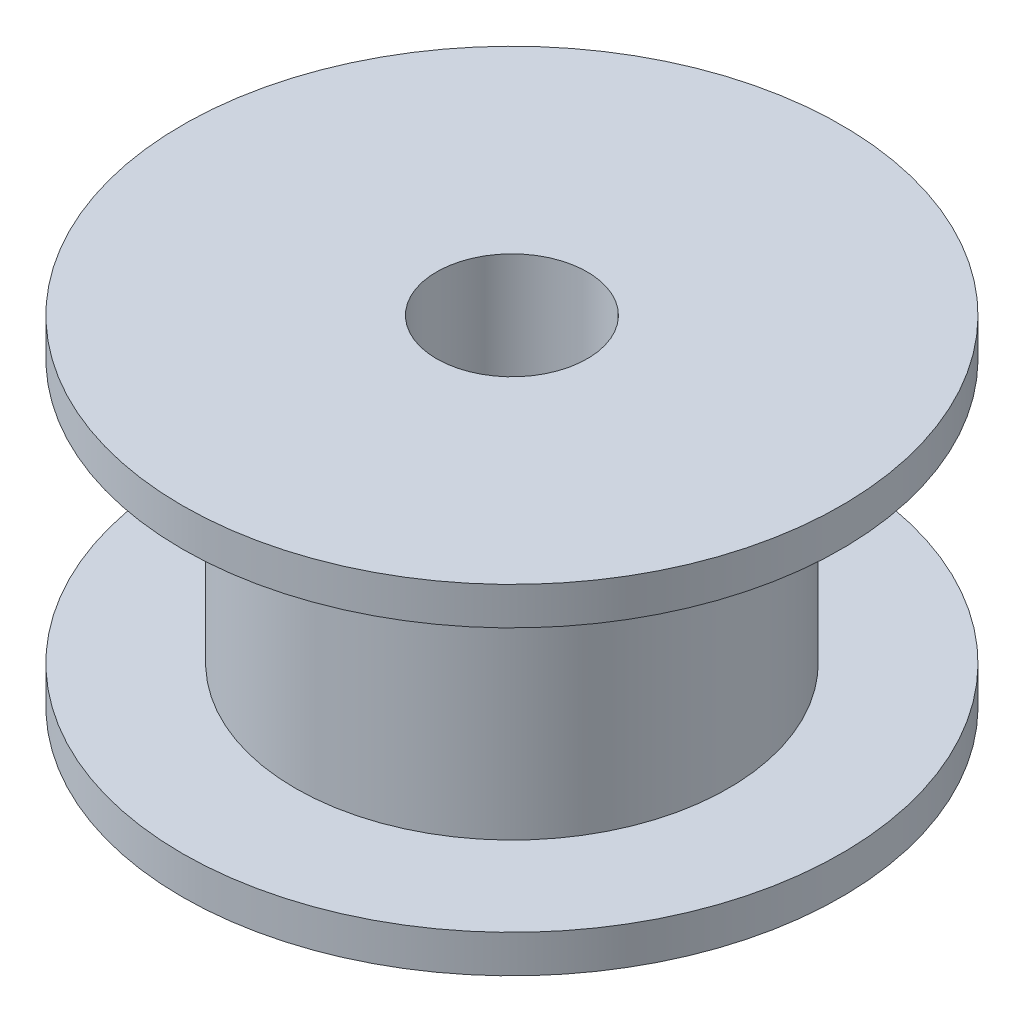
SolidWorks part; units mm, degrees
ref_plane "Спереди" through (0, 0, 0) normal (0, 0, 1) x (1, 0, 0)
ref_plane "Сверху" through (0, 0, 0) normal (0, 1, 0) x (1, 0, 0)
ref_plane "Справа" through (0, 0, 0) normal (1, 0, 0) x (0, 0, -1)
other "Configuration Table"
sketch "Sketch1" plane through (0, 0, 0) normal (0, 0, 1) x (1, 0, 0)
  line L0 (0, 0) -> (2, 0) construction
  line L1 (2, 0) -> (8.75, 0)
  line L2 (8.75, 0) -> (8.75, -1)
  line L3 (8.75, -1) -> (5.75, -1)
  line L4 (5.75, -1) -> (5.75, -8)
  line L5 (5.75, -8) -> (8.75, -8)
  line L6 (8.75, -9) -> (2, -9)
  line L7 (8.75, -8) -> (8.75, -9)
  line L8 (2, -9) -> (2, 0)
  line L9 (0, 0) -> (0, -9) construction
  dimension "D1" = 2
  dimension "D2" = 8.75
  dimension "D3" = 3
  dimension "D4" = 7
  dimension "D5" = 1
  dimension "D6" = 1
revolve "Revolve1" add sketch "Sketch1" angle 360 about L9
